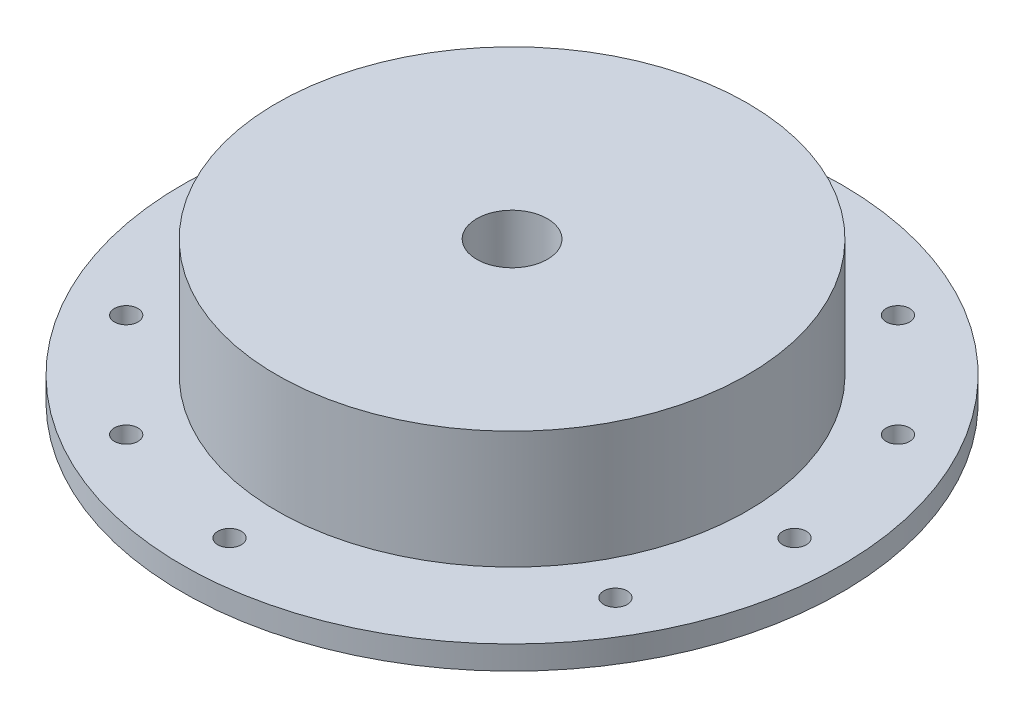
SolidWorks part; units mm, degrees
material "AISI 316 Annealed Stainless Steel Bar (SS)"
ref_plane "Front Plane" through (0, 0, 0) normal (0, 0, 1) x (1, 0, 0)
ref_plane "Top Plane" through (0, 0, 0) normal (0, 1, 0) x (1, 0, 0)
ref_plane "Right Plane" through (0, 0, 0) normal (1, 0, 0) x (0, 0, -1)
sketch "Sketch1" plane through (0, 0, 0) normal (0, 0, 1) x (1, 0, 0)
  line L0 (9.525, 38.1) -> (9.525, 11.1125)
  line L1 (38.1, 0) -> (88.9, 0)
  line L2 (88.9, 0) -> (88.9, 6.35)
  line L3 (88.9, 6.35) -> (63.5, 6.35)
  line L4 (63.5, 6.35) -> (63.5, 38.1)
  line L5 (63.5, 38.1) -> (9.525, 38.1)
  line L6 (0, 0) -> (0, 33.4189) construction
  arc A0 (9.525, 11.1125) -> (38.1, 0) centre (38.1, 42.2955) ccw
  dimension "D1" = 19.05
  dimension "D2" = 177.8
  dimension "D3" = 25.4
  dimension "D4" = 6.35
  dimension "D5" = 38.1
  dimension "D6" = 76.2
  dimension "D7" = 11.1125
revolve "Revolve1" add sketch "Sketch1" angle 360 about L6
sketch "Sketch3" plane through (0, 6.35, 0) normal (0, 1, 0) x (1, 0, 0)
  line L0 (0, 0) -> (0, -101.6) construction
  point P4 (0, -101.6)
  dimension "D1" = 101.6
hole_wizard "1/4 (0.25) Diameter Hole1" positions "Sketch4" profile "Sketch5" hole size "1/4" standard "ANSI Inch" end condition through all
sketch "Sketch4" plane through (0, 6.35, 0) normal (0, 1, 0) x (1, 0, 0)
  line L2 (0, 0) -> (0, -76.2) construction
  point P0 (0, -76.2)
  dimension "D1" = 76.2
sketch "Sketch5" plane through (0, 6.35, 76.2) normal (1, 0, 0) x (0, 0, 1)
  line L0 (0, 0) -> (0, 6.35)
  line L1 (0, 6.35) -> (3.175, 6.35)
  line L2 (3.175, 6.35) -> (3.175, 0)
  line L5 (3.175, 0) -> (0, 0)
  line L11 (0, -6.35) -> (0, 107.95) construction
  dimension "Thru Hole Dia." = 6.35
  dimension "Thru Hole Depth" = 6.35
pattern_circular "CirPattern2" count 12 over 360 about axis through (0, 0, 0) along (0, -1, 0) skipping 1 of "1/4 (0.25) Diameter Hole1"
